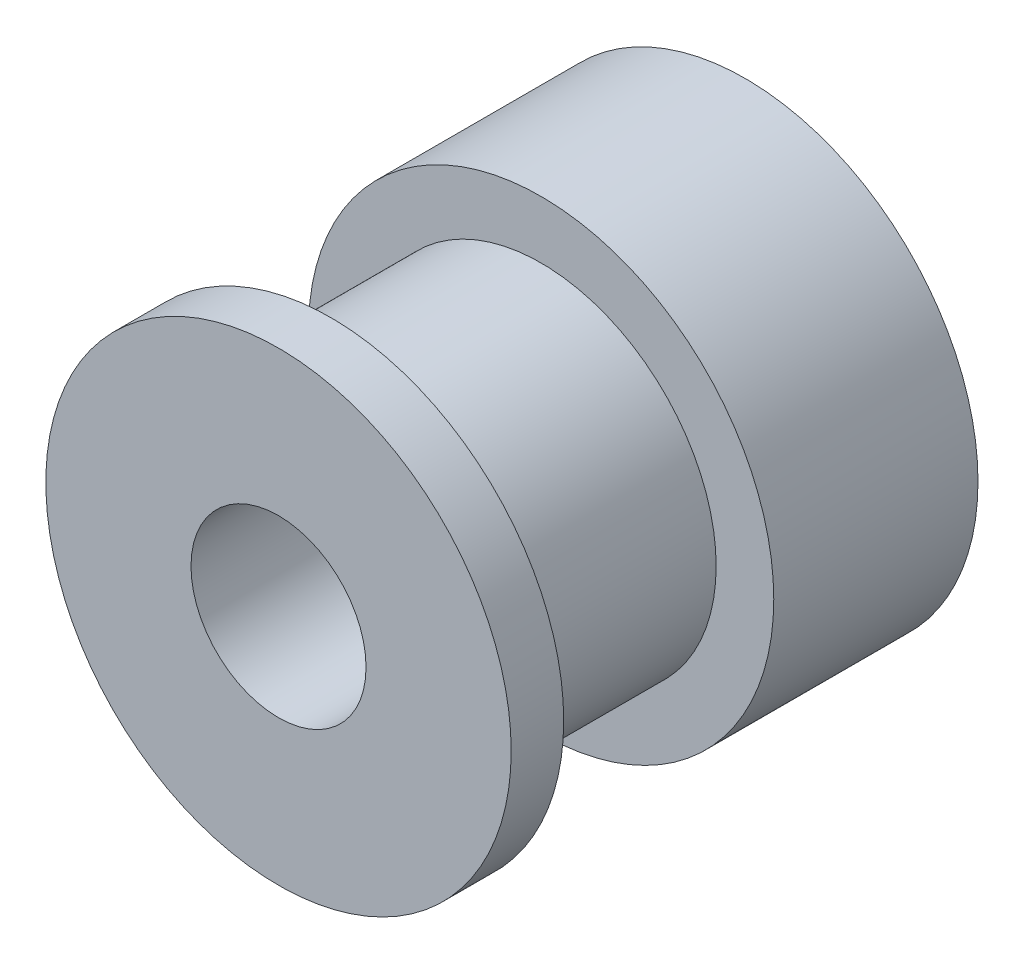
SolidWorks part; units mm, degrees
ref_plane "前视基准面" through (0, 0, 0) normal (0, 0, 1) x (1, 0, 0)
ref_plane "上视基准面" through (0, 0, 0) normal (0, 1, 0) x (1, 0, 0)
ref_plane "右视基准面" through (0, 0, 0) normal (1, 0, 0) x (0, 0, -1)
other "Configuration Table"
sketch "草图1" plane through (0, 0, 0) normal (0, 0, 1) x (1, 0, 0)
  circle A0 centre (0, 0) radius 7.975
  dimension "D1" = 15.95
extrude "凸台-拉伸1" add sketch "草图1" along normal blind 7
sketch "草图2" plane through (0, 0, 7) normal (0, 0, 1) x (1, 0, 0)
  circle A0 centre (0, 0) radius 6
  dimension "D1" = 12
extrude "凸台-拉伸2" add sketch "草图2" along normal blind 7.2
sketch "草图3" plane through (0, 0, 14.2) normal (0, 0, 1) x (1, 0, 0)
  circle A1 centre (0, 0) radius 7.975
  circle A2 centre (0, 0) radius 7.975
  dimension "D1" = 0
extrude "凸台-拉伸3" add sketch "草图3" along normal blind 1.8
sketch "草图4" plane through (0, 0, 16) normal (0, 0, 1) x (1, 0, 0)
  circle A0 centre (0, 0) radius 3
extrude "切除-拉伸1" cut sketch "草图4" against normal through all
